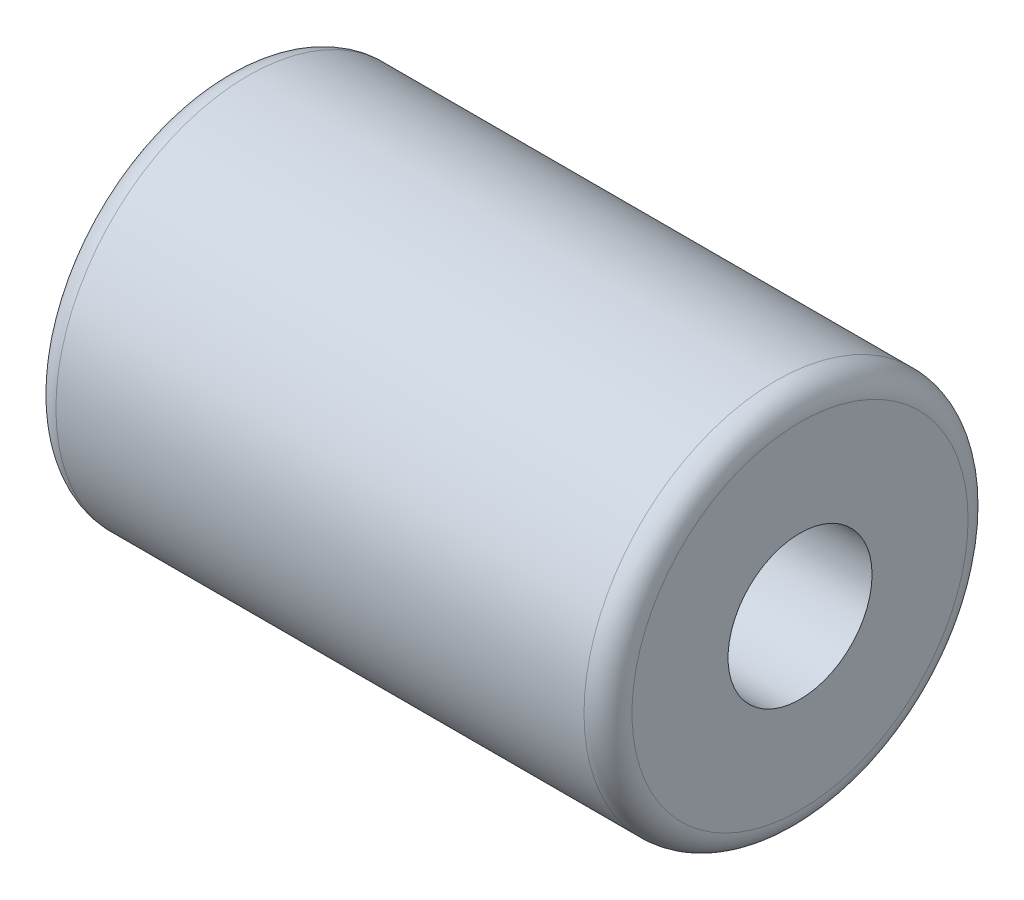
SolidWorks part; units mm, degrees
ref_plane "Alzado" through (0, 0, 0) normal (0, 0, 1) x (1, 0, 0)
ref_plane "Planta" through (0, 0, 0) normal (0, 1, 0) x (1, 0, 0)
ref_plane "Vista lateral" through (0, 0, 0) normal (1, 0, 0) x (0, 0, -1)
sketch "Croquis1" plane through (0, 0, 0) normal (1, 0, 0) x (0, 0, -1)
  circle A0 centre (0, 0) radius 1.5
  circle A1 centre (0, 0) radius 4
  dimension "D1" = 3
  dimension "D2" = 8
extrude "Saliente-Extruir1" add sketch "Croquis1" along normal blind 12
fillet "Redondeo1" radius 0.5 2 edges at (0, 0, -4) (12, 0, -4)
